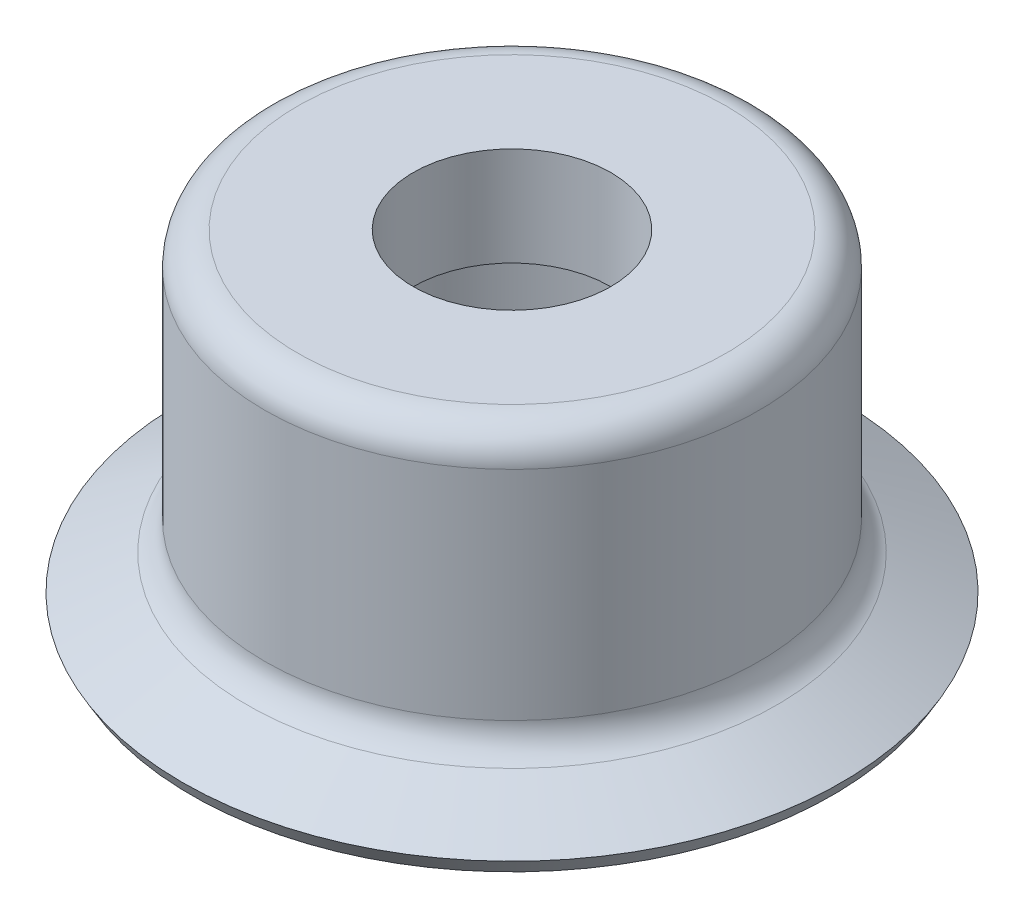
SolidWorks part; units mm, degrees
ref_plane "前视基准面" through (0, 0, 0) normal (0, 0, 1) x (1, 0, 0)
ref_plane "上视基准面" through (0, 0, 0) normal (0, 1, 0) x (1, 0, 0)
ref_plane "右视基准面" through (0, 0, 0) normal (1, 0, 0) x (0, 0, -1)
sketch "草图1" plane through (0, 0, 0) normal (0, 0, 1) x (1, 0, 0)
  line L0 (3, 7) -> (5, 7)
  line L1 (5, 7) -> (5, 1.5)
  line L2 (5, 1.5) -> (9.1212, 0)
  line L3 (9.1212, 0) -> (9.7282, 0)
  line L4 (9.7282, 0) -> (10, 0.4707)
  line L5 (10, 0.4707) -> (8.0305, 1.5179)
  line L6 (7.5, 2.4009) -> (7.5, 9)
  line L7 (6.5, 10) -> (3, 10)
  line L8 (3, 10) -> (3, 7)
  line L9 (0, 10.0013) -> (0, 0) construction
  arc A0 (8.0305, 1.5179) -> (7.5, 2.4009) centre (8.5, 2.4009) cw
  arc A1 (7.5, 9) -> (6.5, 10) centre (6.5, 9) ccw
revolve "旋转1" add sketch "草图1" angle 360 about L9
